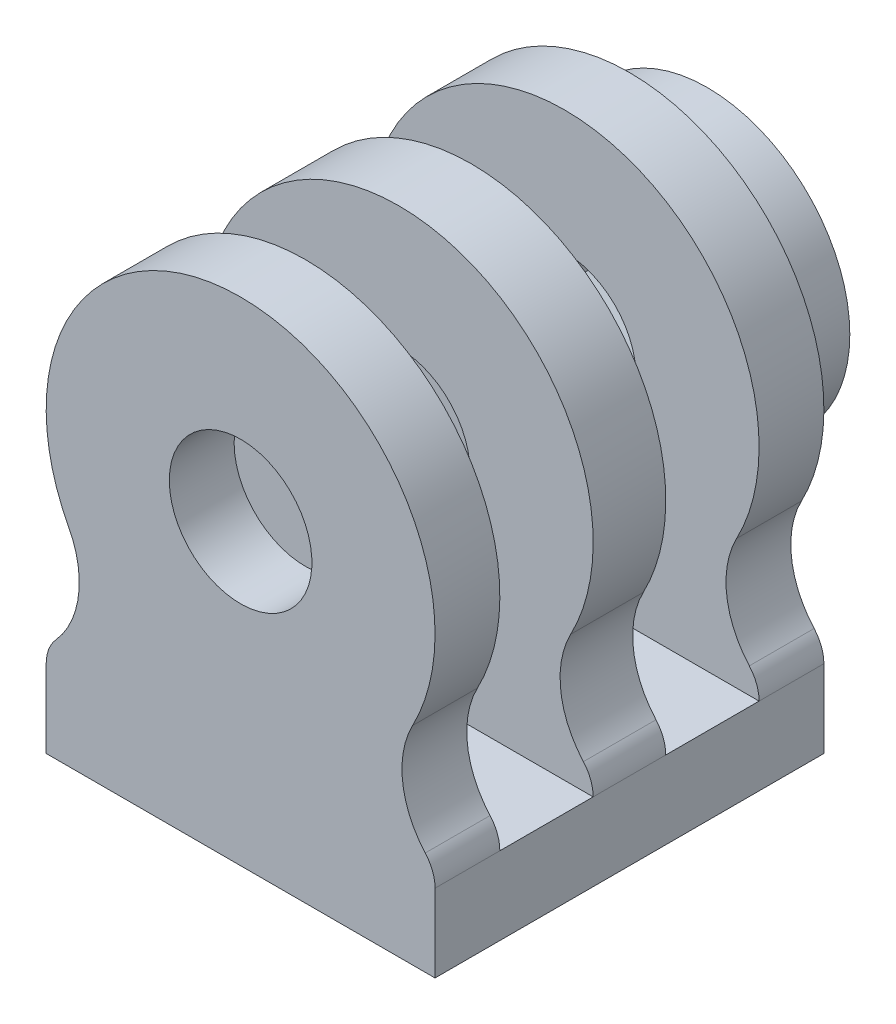
SolidWorks part; units mm, degrees
ref_plane "Front Plane" through (0, 0, 0) normal (0, 0, 1) x (1, 0, 0)
ref_plane "Top Plane" through (0, 0, 0) normal (0, 1, 0) x (1, 0, 0)
ref_plane "Right Plane" through (0, 0, 0) normal (1, 0, 0) x (0, 0, -1)
sketch "Sketch1" plane through (0, 0, 0) normal (0, 1, 0) x (1, 0, 0)
  line L1 (0, 0) -> (15, 0)
  line L2 (0, 0) -> (0, 7.5)
  line L3 (0, 7.5) -> (15, 7.5)
  line L4 (15, 0) -> (15, 7.5)
  dimension "D1" = 7.5
  dimension "D2" = 15
extrude "Boss-Extrude - Base" add sketch "Sketch1" along normal blind 3
sketch "Sketch2" plane through (0, 3, 0) normal (0, 1, 0) x (1, 0, 0)
  line L0 (15, 0) -> (15, 7.5) construction
  line L1 (0, 7.5) -> (15, 7.5)
  line L2 (0, 7.5) -> (0, 5)
  line L3 (0, 5) -> (15, 5)
  line L4 (15, 7.5) -> (15, 5)
  line L6 (0, 0) -> (15, 0)
  line L7 (0, 0) -> (0, 1.4)
  line L8 (0, 1.4) -> (15, 1.4)
  line L9 (15, 0) -> (15, 1.4)
  dimension "D1" = 2.5
  dimension "D2" = 1.4
extrude "Boss-Extrude2" add sketch "Sketch2" along normal blind 16
sketch "Sketch4" plane through (0, 0, -7.5) normal (0, 0, -1) x (-1, 0, 0)
  line L0 (0, 3) -> (3.145, 3)
  line L1 (-15, 19) -> (-15, 0) construction
  line L3 (3.145, 3) -> (3.145, 20.6554)
  line L4 (-18.1549, 20.6554) -> (3.145, 20.6554)
  line L8 (0, 19) -> (0, 0) construction
  line L9 (-15, 19) -> (0, 19) construction
  line L10 (-15, 3) -> (-18.1549, 3)
  line L11 (-18.1549, 3) -> (-18.1549, 20.6554)
  arc A0 (-14.1332, 8) -> (-0.8668, 8) centre (-7.5, 11.5) cw
  arc A1 (-14.1332, 8) -> (-14.6231, 3.9887) centre (-17.2661, 6.347) cw
  arc A2 (-14.6231, 3.9887) -> (-15, 3) centre (-13.515, 3) ccw
  arc A3 (-0.8668, 8) -> (-0.3769, 3.9887) centre (2.2661, 6.347) ccw
  arc A4 (-0.3769, 3.9887) -> (0, 3) centre (-1.485, 3) cw
  point P25 (-13.75, 5.9176)
  point P26 (-1.25, 5.9176)
  dimension "D1" = 11
  dimension "D2" = 12.5
extrude "Cut-Extrude1" cut sketch "Sketch4" against normal through all
sketch "Sketch6" plane through (0, 0, -7.5) normal (0, 0, -1) x (-1, 0, 0)
  circle A0 centre (-7.5, 11.5) radius 2.75
  arc A4 (-0.8668, 8) -> (-14.1332, 8) centre (-7.5, 11.5) ccw construction
  dimension "D2" = 5.5
extrude "Cut-Extrude - Hole" cut sketch "Sketch6" against normal through all
mirror "Mirror1" about plane through (0, 3, 0) normal (0, 0, -1) of bodies 106
sketch "Sketch7" plane through (0, 0, -7.5) normal (0, 0, -1) x (-1, 0, 0)
  circle A0 centre (-7.5, 11.5) radius 5.5
  dimension "D1" = 11
extrude "Boss-Extrude4" add sketch "Sketch7" along normal blind 3
sketch "Sketch8" plane through (0, 0, -10.5) normal (0, 0, -1) x (-1, 0, 0)
  line L1 (-3.5, 9.1906) -> (-3.5, 13.8094)
  line L2 (-3.5, 13.8094) -> (-7.5, 16.1188)
  line L3 (-7.5, 16.1188) -> (-11.5, 13.8094)
  line L4 (-11.5, 13.8094) -> (-11.5, 9.1906)
  line L5 (-11.5, 9.1906) -> (-7.5, 6.8812)
  line L6 (-7.5, 6.8812) -> (-3.5, 9.1906)
  circle A0 centre (-7.5, 11.5) radius 4 construction
  dimension "D1" = 8
extrude "Cut-Extrude4" cut sketch "Sketch8" against normal up to surface (3 mm away) up to face at (2, 11.5, -7.5)
